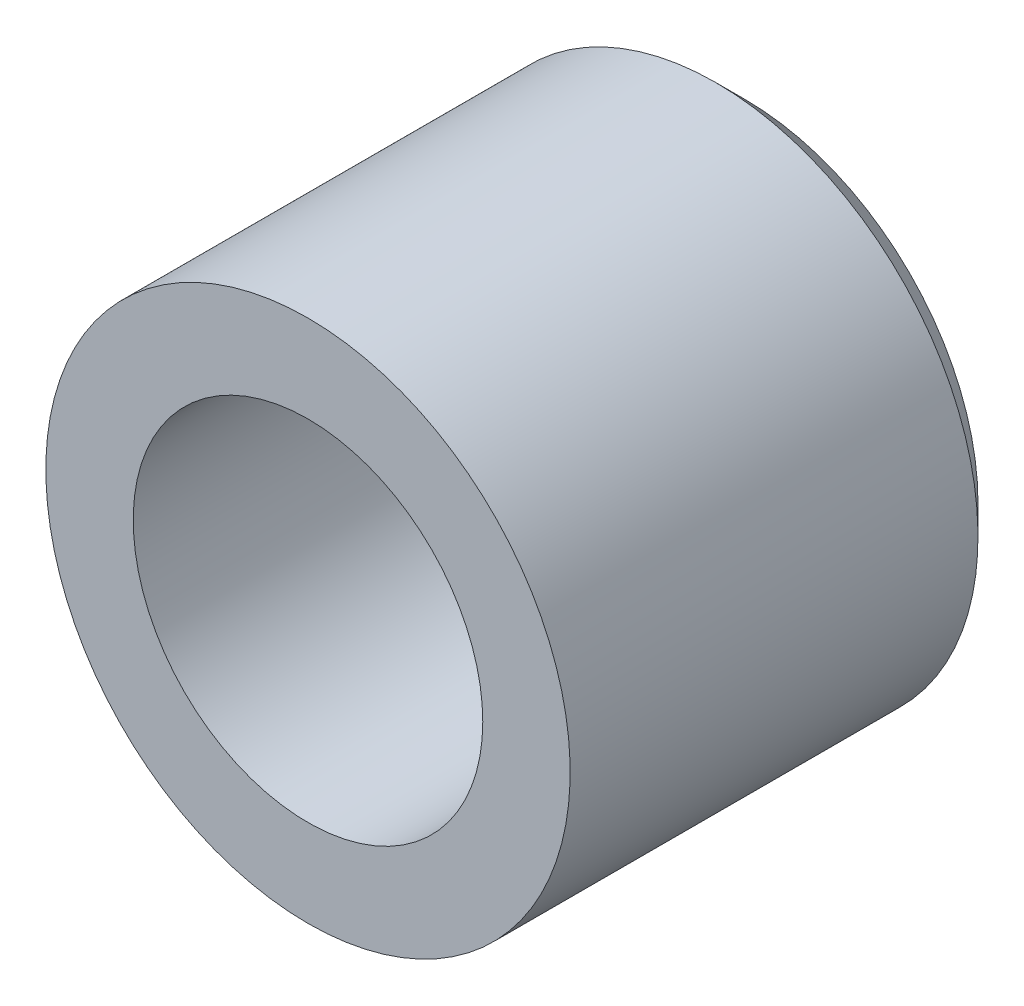
SolidWorks part; units mm, degrees
ref_plane "前视基准面" through (0, 0, 0) normal (0, 0, 1) x (1, 0, 0)
ref_plane "上视基准面" through (0, 0, 0) normal (0, 1, 0) x (1, 0, 0)
ref_plane "右视基准面" through (0, 0, 0) normal (1, 0, 0) x (0, 0, -1)
sketch "草图1" plane through (0, 0, 0) normal (1, 0, 0) x (0, 0, -1)
  line L1 (0, -6) -> (-15, -6)
  line L2 (0, -6) -> (0, -9)
  line L3 (0, -9) -> (-15, -9)
  line L5 (-15, -9) -> (-15, 0)
  line L7 (-18, -9) -> (-15, -9)
  line L8 (0, 0) -> (-15, 0) construction
  line L10 (-18, -9) -> (-18, 0)
  line L11 (-18, 0) -> (-15, 0)
  dimension "D1" = 18
  dimension "D" = 12
  dimension "L" = 15
  dimension "D10" = 3
revolve "旋转1" add sketch "草图1" angle 360 mid plane about L8
sketch "草图2" plane through (0, 0, 0) normal (1, 0, 0) x (0, 0, -1)
  line L0 (0, 0) -> (-18, 0) construction
  line L1 (-18, 0) -> (-15, 0)
  line L2 (-18, 0) -> (-18, -6.5)
  line L3 (-18, -6.5) -> (-15, -6.5)
  line L4 (-15, 0) -> (-15, -6.5)
  line L5 (0, 0) -> (-15, 0) construction
  line L7 (-15, -9) -> (-15, 0) construction
  dimension "D1" = 3
  dimension "D2" = 13
  dimension "L1" = 15
revolve "切除-旋转1" cut sketch "草图2" angle 360 mid plane about L1
sketch "草图3" plane through (0, 0, 0) normal (1, 0, 0) x (0, 0, -1)
  line L0 (-18, -9) -> (-18, 0) construction
  line L1 (-18, 0) -> (-15, 0) construction
  line L2 (-15, -9) -> (-15, 0) construction
  line L3 (-18, -9) -> (-15, -9) construction
  line L4 (-18, -9) -> (-18, 0)
  line L5 (-18, 0) -> (-15, 0)
  line L6 (-15, -9) -> (-15, 0)
  line L7 (-18, -9) -> (-15, -9)
revolve "切除-旋转2" cut sketch "草图3" angle 360 mid plane about L5
chamfer "倒角1" distance 1 angle 45 1 edges at (0, 9, 0)
fillet "圆角2" radius 1.5 1 edges at (0, 6, 0)
